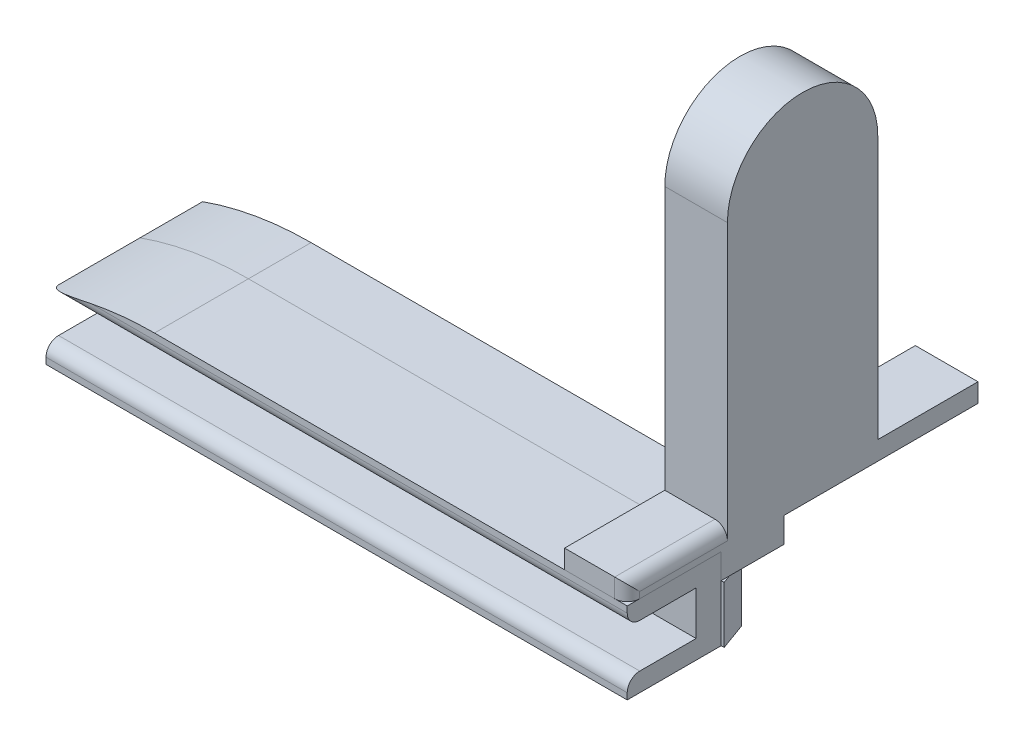
SolidWorks part; units mm, degrees
material "ABS"
ref_plane "Front Plane" through (0, 0, 0) normal (0, 0, 1) x (1, 0, 0)
ref_plane "Top Plane" through (0, 0, 0) normal (0, 1, 0) x (1, 0, 0)
ref_plane "Right Plane" through (0, 0, 0) normal (1, 0, 0) x (0, 0, -1)
sketch "Sketch1" plane through (0, 0, 0) normal (0, 1, 0) x (1, 0, 0)
  line L1 (-63.8587, 6.2481) -> (1.1413, 6.2481)
  line L2 (-63.8587, 6.2481) -> (-63.8587, 4.2481)
  line L3 (-63.8587, 4.2481) -> (1.1413, 4.2481)
  line L4 (1.1413, 6.2481) -> (1.1413, 4.2481)
  dimension "D1" = 65
  dimension "D2" = 2
extrude "Boss-Extrude1" add sketch "Sketch1" along normal blind 6.5
sketch "Sketch2" plane through (0, 0, 0) normal (0, 1, 0) x (1, 0, 0)
  line L0 (-63.8587, 6.2481) -> (-62.6387, 9.6031) construction
  line L1 (-62.6387, 9.6031) -> (-61.4187, 6.2481) construction
  line L2 (1.1413, 6.2481) -> (-63.8587, 6.2481) construction
  line L3 (-63.8587, 6.2481) -> (-61.4187, 6.2481)
  line L4 (-62.6387, 9.6031) -> (-62.6387, 6.2481) construction
  line L5 (-63.0587, 8.4481) -> (-62.2187, 8.4481)
  line L6 (-63.0587, 8.4481) -> (-63.8587, 6.2481)
  line L7 (-62.2187, 8.4481) -> (-61.4187, 6.2481)
  line L8 (-60.7187, 6.2481) -> (-58.2787, 6.2481)
  line L9 (-59.9187, 8.4481) -> (-60.7187, 6.2481)
  line L10 (-59.0787, 8.4481) -> (-58.2787, 6.2481)
  line L11 (-60.7187, 6.2481) -> (-59.4987, 9.6031) construction
  line L12 (-59.4987, 9.6031) -> (-58.2787, 6.2481) construction
  line L13 (-59.4987, 9.6031) -> (-59.4987, 6.2481) construction
  line L14 (-59.9187, 8.4481) -> (-59.0787, 8.4481)
  line L15 (-57.5787, 6.2481) -> (-55.1387, 6.2481)
  line L16 (-56.7787, 8.4481) -> (-57.5787, 6.2481)
  line L17 (-55.9387, 8.4481) -> (-55.1387, 6.2481)
  line L18 (-57.5787, 6.2481) -> (-56.3587, 9.6031) construction
  line L19 (-56.3587, 9.6031) -> (-55.1387, 6.2481) construction
  line L20 (-56.3587, 9.6031) -> (-56.3587, 6.2481) construction
  line L21 (-56.7787, 8.4481) -> (-55.9387, 8.4481)
  line L22 (-54.4387, 6.2481) -> (-51.9987, 6.2481)
  line L23 (-53.6387, 8.4481) -> (-54.4387, 6.2481)
  line L24 (-52.7987, 8.4481) -> (-51.9987, 6.2481)
  line L25 (-54.4387, 6.2481) -> (-53.2187, 9.6031) construction
  line L26 (-53.2187, 9.6031) -> (-51.9987, 6.2481) construction
  line L27 (-53.2187, 9.6031) -> (-53.2187, 6.2481) construction
  line L28 (-53.6387, 8.4481) -> (-52.7987, 8.4481)
  line L29 (-51.2987, 6.2481) -> (-48.8587, 6.2481)
  line L30 (-50.4987, 8.4481) -> (-51.2987, 6.2481)
  line L31 (-49.6587, 8.4481) -> (-48.8587, 6.2481)
  line L32 (-51.2987, 6.2481) -> (-50.0787, 9.6031) construction
  line L33 (-50.0787, 9.6031) -> (-48.8587, 6.2481) construction
  line L34 (-50.0787, 9.6031) -> (-50.0787, 6.2481) construction
  line L35 (-50.4987, 8.4481) -> (-49.6587, 8.4481)
  line L36 (-48.1587, 6.2481) -> (-45.7187, 6.2481)
  line L37 (-47.3587, 8.4481) -> (-48.1587, 6.2481)
  line L38 (-46.5187, 8.4481) -> (-45.7187, 6.2481)
  line L39 (-48.1587, 6.2481) -> (-46.9387, 9.6031) construction
  line L40 (-46.9387, 9.6031) -> (-45.7187, 6.2481) construction
  line L41 (-46.9387, 9.6031) -> (-46.9387, 6.2481) construction
  line L42 (-47.3587, 8.4481) -> (-46.5187, 8.4481)
  line L43 (-45.0187, 6.2481) -> (-42.5787, 6.2481)
  line L44 (-44.2187, 8.4481) -> (-45.0187, 6.2481)
  line L45 (-43.3787, 8.4481) -> (-42.5787, 6.2481)
  line L46 (-45.0187, 6.2481) -> (-43.7987, 9.6031) construction
  line L47 (-43.7987, 9.6031) -> (-42.5787, 6.2481) construction
  line L48 (-43.7987, 9.6031) -> (-43.7987, 6.2481) construction
  line L49 (-44.2187, 8.4481) -> (-43.3787, 8.4481)
  line L50 (-41.8787, 6.2481) -> (-39.4387, 6.2481)
  line L51 (-41.0787, 8.4481) -> (-41.8787, 6.2481)
  line L52 (-40.2387, 8.4481) -> (-39.4387, 6.2481)
  line L53 (-41.8787, 6.2481) -> (-40.6587, 9.6031) construction
  line L54 (-40.6587, 9.6031) -> (-39.4387, 6.2481) construction
  line L55 (-40.6587, 9.6031) -> (-40.6587, 6.2481) construction
  line L56 (-41.0787, 8.4481) -> (-40.2387, 8.4481)
  line L57 (-38.7387, 6.2481) -> (-36.2987, 6.2481)
  line L58 (-37.9387, 8.4481) -> (-38.7387, 6.2481)
  line L59 (-37.0987, 8.4481) -> (-36.2987, 6.2481)
  line L60 (-38.7387, 6.2481) -> (-37.5187, 9.6031) construction
  line L61 (-37.5187, 9.6031) -> (-36.2987, 6.2481) construction
  line L62 (-37.5187, 9.6031) -> (-37.5187, 6.2481) construction
  line L63 (-37.9387, 8.4481) -> (-37.0987, 8.4481)
  line L64 (-35.5987, 6.2481) -> (-33.1587, 6.2481)
  line L65 (-34.7987, 8.4481) -> (-35.5987, 6.2481)
  line L66 (-33.9587, 8.4481) -> (-33.1587, 6.2481)
  line L67 (-35.5987, 6.2481) -> (-34.3787, 9.6031) construction
  line L68 (-34.3787, 9.6031) -> (-33.1587, 6.2481) construction
  line L69 (-34.3787, 9.6031) -> (-34.3787, 6.2481) construction
  line L70 (-34.7987, 8.4481) -> (-33.9587, 8.4481)
  line L71 (-32.4587, 6.2481) -> (-30.0187, 6.2481)
  line L72 (-31.6587, 8.4481) -> (-32.4587, 6.2481)
  line L73 (-30.8187, 8.4481) -> (-30.0187, 6.2481)
  line L74 (-32.4587, 6.2481) -> (-31.2387, 9.6031) construction
  line L75 (-31.2387, 9.6031) -> (-30.0187, 6.2481) construction
  line L76 (-31.2387, 9.6031) -> (-31.2387, 6.2481) construction
  line L77 (-31.6587, 8.4481) -> (-30.8187, 8.4481)
  line L78 (-29.3187, 6.2481) -> (-26.8787, 6.2481)
  line L79 (-28.5187, 8.4481) -> (-29.3187, 6.2481)
  line L80 (-27.6787, 8.4481) -> (-26.8787, 6.2481)
  line L81 (-29.3187, 6.2481) -> (-28.0987, 9.6031) construction
  line L82 (-28.0987, 9.6031) -> (-26.8787, 6.2481) construction
  line L83 (-28.0987, 9.6031) -> (-28.0987, 6.2481) construction
  line L84 (-28.5187, 8.4481) -> (-27.6787, 8.4481)
  line L85 (-26.1787, 6.2481) -> (-23.7387, 6.2481)
  line L86 (-25.3787, 8.4481) -> (-26.1787, 6.2481)
  line L87 (-24.5387, 8.4481) -> (-23.7387, 6.2481)
  line L88 (-26.1787, 6.2481) -> (-24.9587, 9.6031) construction
  line L89 (-24.9587, 9.6031) -> (-23.7387, 6.2481) construction
  line L90 (-24.9587, 9.6031) -> (-24.9587, 6.2481) construction
  line L91 (-25.3787, 8.4481) -> (-24.5387, 8.4481)
  line L92 (-23.0387, 6.2481) -> (-20.5987, 6.2481)
  line L93 (-22.2387, 8.4481) -> (-23.0387, 6.2481)
  line L94 (-21.3987, 8.4481) -> (-20.5987, 6.2481)
  line L95 (-23.0387, 6.2481) -> (-21.8187, 9.6031) construction
  line L96 (-21.8187, 9.6031) -> (-20.5987, 6.2481) construction
  line L97 (-21.8187, 9.6031) -> (-21.8187, 6.2481) construction
  line L98 (-22.2387, 8.4481) -> (-21.3987, 8.4481)
  line L99 (-19.8987, 6.2481) -> (-17.4587, 6.2481)
  line L100 (-19.0987, 8.4481) -> (-19.8987, 6.2481)
  line L101 (-18.2587, 8.4481) -> (-17.4587, 6.2481)
  line L102 (-19.8987, 6.2481) -> (-18.6787, 9.6031) construction
  line L103 (-18.6787, 9.6031) -> (-17.4587, 6.2481) construction
  line L104 (-18.6787, 9.6031) -> (-18.6787, 6.2481) construction
  line L105 (-19.0987, 8.4481) -> (-18.2587, 8.4481)
  line L106 (-16.7587, 6.2481) -> (-14.3187, 6.2481)
  line L107 (-15.9587, 8.4481) -> (-16.7587, 6.2481)
  line L108 (-15.1187, 8.4481) -> (-14.3187, 6.2481)
  line L109 (-16.7587, 6.2481) -> (-15.5387, 9.6031) construction
  line L110 (-15.5387, 9.6031) -> (-14.3187, 6.2481) construction
  line L111 (-15.5387, 9.6031) -> (-15.5387, 6.2481) construction
  line L112 (-15.9587, 8.4481) -> (-15.1187, 8.4481)
  line L113 (-13.6187, 6.2481) -> (-11.1787, 6.2481)
  line L114 (-12.8187, 8.4481) -> (-13.6187, 6.2481)
  line L115 (-11.9787, 8.4481) -> (-11.1787, 6.2481)
  line L116 (-13.6187, 6.2481) -> (-12.3987, 9.6031) construction
  line L117 (-12.3987, 9.6031) -> (-11.1787, 6.2481) construction
  line L118 (-12.3987, 9.6031) -> (-12.3987, 6.2481) construction
  line L119 (-12.8187, 8.4481) -> (-11.9787, 8.4481)
  line L120 (-10.4787, 6.2481) -> (-8.0387, 6.2481)
  line L121 (-9.6787, 8.4481) -> (-10.4787, 6.2481)
  line L122 (-8.8387, 8.4481) -> (-8.0387, 6.2481)
  line L123 (-10.4787, 6.2481) -> (-9.2587, 9.6031) construction
  line L124 (-9.2587, 9.6031) -> (-8.0387, 6.2481) construction
  line L125 (-9.2587, 9.6031) -> (-9.2587, 6.2481) construction
  line L126 (-9.6787, 8.4481) -> (-8.8387, 8.4481)
  line L127 (-7.3387, 6.2481) -> (-4.8987, 6.2481)
  line L128 (-6.5387, 8.4481) -> (-7.3387, 6.2481)
  line L129 (-5.6987, 8.4481) -> (-4.8987, 6.2481)
  line L130 (-7.3387, 6.2481) -> (-6.1187, 9.6031) construction
  line L131 (-6.1187, 9.6031) -> (-4.8987, 6.2481) construction
  line L132 (-6.1187, 9.6031) -> (-6.1187, 6.2481) construction
  line L133 (-6.5387, 8.4481) -> (-5.6987, 8.4481)
  line L134 (-4.1987, 6.2481) -> (-1.7587, 6.2481)
  line L135 (-3.3987, 8.4481) -> (-4.1987, 6.2481)
  line L136 (-2.5587, 8.4481) -> (-1.7587, 6.2481)
  line L137 (-4.1987, 6.2481) -> (-2.9787, 9.6031) construction
  line L138 (-2.9787, 9.6031) -> (-1.7587, 6.2481) construction
  line L139 (-2.9787, 9.6031) -> (-2.9787, 6.2481) construction
  line L140 (-3.3987, 8.4481) -> (-2.5587, 8.4481)
  line L141 (-1.0587, 6.2481) -> (1.3813, 6.2481)
  line L142 (-0.2587, 8.4481) -> (-1.0587, 6.2481)
  line L143 (0.5813, 8.4481) -> (1.3813, 6.2481)
  line L144 (-1.0587, 6.2481) -> (0.1613, 9.6031) construction
  line L145 (0.1613, 9.6031) -> (1.3813, 6.2481) construction
  line L146 (0.1613, 9.6031) -> (0.1613, 6.2481) construction
  line L147 (-0.2587, 8.4481) -> (0.5813, 8.4481)
  line L148 (2.0813, 6.2481) -> (4.5213, 6.2481)
  line L149 (2.8813, 8.4481) -> (2.0813, 6.2481)
  line L150 (3.7213, 8.4481) -> (4.5213, 6.2481)
  line L151 (2.0813, 6.2481) -> (3.3013, 9.6031) construction
  line L152 (3.3013, 9.6031) -> (4.5213, 6.2481) construction
  line L153 (3.3013, 9.6031) -> (3.3013, 6.2481) construction
  line L154 (2.8813, 8.4481) -> (3.7213, 8.4481)
  line L155 (5.2213, 6.2481) -> (7.6613, 6.2481)
  line L156 (6.0213, 8.4481) -> (5.2213, 6.2481)
  line L157 (6.8613, 8.4481) -> (7.6613, 6.2481)
  line L158 (5.2213, 6.2481) -> (6.4413, 9.6031) construction
  line L159 (6.4413, 9.6031) -> (7.6613, 6.2481) construction
  line L160 (6.4413, 9.6031) -> (6.4413, 6.2481) construction
  line L161 (6.0213, 8.4481) -> (6.8613, 8.4481)
  dimension "D1" = 2.44
  dimension "D2" = 2.2
  dimension "D3" = 0.84
  dimension "D5" = 0.7
  dimension "D4" = 23
extrude "Boss-Extrude2" add sketch "Sketch2" along normal blind 4.5
sketch "Sketch5" plane through (0, 0, -4.2481) normal (0, 0, 1) x (1, 0, 0)
  line L0 (-65.8587, 15) -> (-65.8587, 0) construction
  line L1 (-65.8587, 0) -> (1.1413, 0)
  line L2 (-65.8587, 0) -> (-65.8587, 1.5)
  line L3 (-65.8587, 1.5) -> (1.1413, 1.5)
  line L4 (1.1413, 0) -> (1.1413, 1.5)
  line L5 (1.1413, 6.5) -> (-65.8587, 6.5)
  line L6 (1.1413, 6.5) -> (1.1413, 5)
  line L7 (1.1413, 5) -> (-65.8587, 5)
  line L8 (-65.8587, 6.5) -> (-65.8587, 5)
  line L9 (1.1413, 6.5) -> (1.1413, 0) construction
  line L11 (-63.8587, 6.5) -> (1.1413, 6.5) construction
  dimension "D1" = 1.5
extrude "Boss-Extrude6" add sketch "Sketch5" along normal blind 5.5
sketch "Sketch6" plane through (1.1413, 0, 0) normal (1, 0, 0) x (0, 0, -1)
  line L0 (6.2481, 6.5) -> (26.7481, 6.5)
  line L1 (6.2481, 6.5) -> (-1.2519, 6.5)
  line L2 (6.7481, 8) -> (6.7481, 29)
  line L3 (18.7481, 8) -> (18.7481, 29)
  line L4 (12.7481, 35) -> (12.7481, 6.5) construction
  line L5 (18.7481, 8) -> (6.7481, 8) construction
  line L6 (26.7481, 6.5) -> (26.7481, 8)
  line L7 (-1.2519, 6.5) -> (-1.2519, 8)
  line L8 (-1.2519, 8) -> (6.7481, 8)
  line L9 (26.7481, 8) -> (18.7481, 8)
  arc A2 (6.7481, 29) -> (18.7481, 29) centre (12.7481, 29) cw
  dimension "D1" = 12
  dimension "D2" = 27
  dimension "D3" = 1.5
  dimension "D4" = 28
extrude "Boss-Extrude7" add sketch "Sketch6" against normal blind 5 separate body
sketch "Sketch7" plane through (0, 0, -6.2481) normal (0, 0, -1) x (-1, 0, 0)
  line L0 (63.8587, 4.5) -> (63.8587, 0) construction
  line L1 (-1.1413, 6.5) -> (63.8587, 6.5)
  line L2 (-1.1413, 6.5) -> (-1.1413, 4.5)
  line L3 (-1.1413, 4.5) -> (63.8587, 4.5)
  line L4 (63.8587, 6.5) -> (63.8587, 4.5)
  dimension "D1" = 2
extrude "Boss-Extrude8" add sketch "Sketch7" along normal blind 5
sketch "Sketch8" plane through (0, 0, 0) normal (0, -1, 0) x (-1, 0, 0)
  line L1 (45.253, 19.949) -> (76.6817, 19.949)
  line L2 (45.253, 19.949) -> (45.253, -9.1419)
  line L3 (45.253, -9.1419) -> (76.6817, -9.1419)
  line L4 (76.6817, 19.949) -> (76.6817, -9.1419)
extrude "Cut-Extrude1" cut sketch "Sketch8" against normal through all
sketch "Sketch10" plane through (0, 0, 1.2519) normal (0, 0, 1) x (1, 0, 0)
  line L0 (1.1413, 6.5) -> (-45.253, 6.5) construction
  line L1 (-45.253, 5) -> (-45.253, 6.5)
  line L2 (-45.253, 6.5) -> (-36.5934, 6.5)
  arc A0 (-36.5934, 6.5) -> (-45.253, 5) centre (-36.5934, -19.2467) ccw
  line M1 (1.1413, 6.5) -> (-45.253, 6.5)
  line M2 (-45.253, 6.5) -> (-45.253, 5)
extrude "Cut-Extrude2" cut sketch "Sketch10" along direction (0, 0, -1) on the side against the normal through all contours A0 M1 M2
fillet "Fillet5" radius 1 2 edges at (1.1413, 7.25, 1.2519) (1.1413, 8, -2.7481)
fillet "Fillet7" radius 1 2 edges at (-22.0559, 5, 1.2519) (-22.0559, 1.5, 1.2519)
